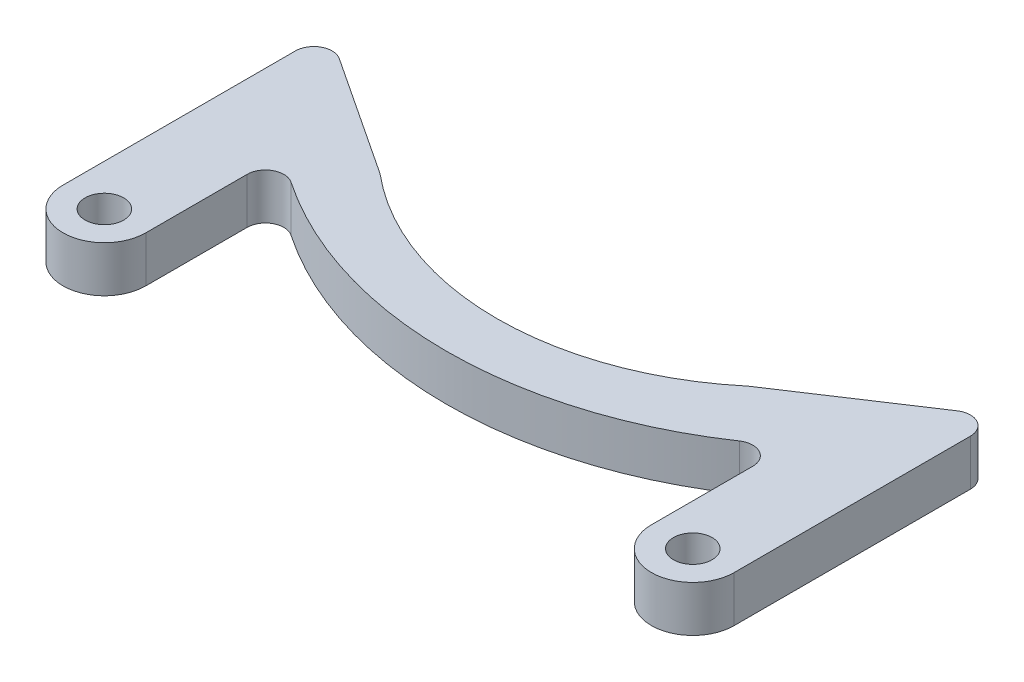
SolidWorks part; units mm, degrees
ref_plane "Front" through (0, 0, 0) normal (0, 0, 1) x (1, 0, 0)
ref_plane "Top" through (0, 0, 0) normal (0, 1, 0) x (1, 0, 0)
ref_plane "Right" through (0, 0, 0) normal (1, 0, 0) x (0, 0, -1)
sketch "Sketch1" plane through (0, 0, 0) normal (0, 1, 0) x (1, 0, 0)
  line L3 (68.5, 0) -> (68.5, 15)
  line L13 (68.5, 24.6393) -> (68.5, 15)
  line L14 (11.6771, 18.3085) -> (-4.5, 28.9934)
  line L16 (51.6805, 18.3085) -> (68.5, 29.4177)
  line L17 (68.5, 29.4177) -> (68.5, 24.6393)
  line L20 (4.5, 0) -> (4.5, 15)
  line L21 (-4.5, 0) -> (-4.5, 28.9934)
  line L22 (59.5, 0) -> (59.5, 15)
  circle A0 centre (0, 0) radius 2.1
  circle A1 centre (64, 0) radius 2.1
  arc A7 (11.6771, 18.3085) -> (51.6805, 18.3085) centre (31.6788, 42.1094) ccw
  arc A9 (-4.5, 0) -> (4.5, 0) centre (0, 0) ccw
  arc A10 (59.5, 0) -> (68.5, 0) centre (64, 0) ccw
  arc A11 (4.5, 15) -> (59.5, 15) centre (32, 48.6912) ccw
extrude "Boss-Extrude1" add sketch "Sketch1" along normal blind 5
fillet "Fillet2" radius 2 6 edges at (11.6771, 2.5, -18.3085) (51.6805, 2.5, -18.3085) (68.5, 2.5, -29.4177) (59.5, 2.5, -15) (4.5, 2.5, -15) (-4.5, 2.5, -28.9934)
